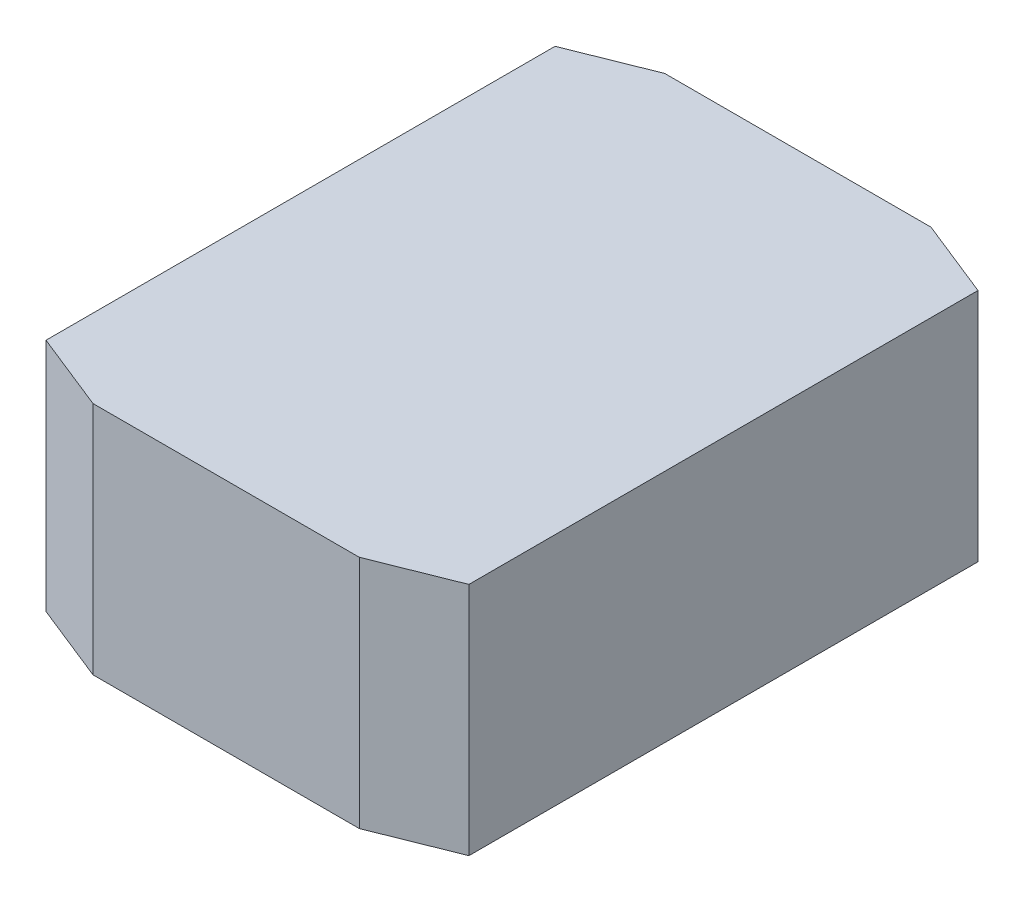
SolidWorks part; units mm, degrees
ref_plane "Piano frontale" through (0, 0, 0) normal (0, 0, 1) x (1, 0, 0)
ref_plane "Piano superiore" through (0, 0, 0) normal (0, 1, 0) x (1, 0, 0)
ref_plane "Piano destro" through (0, 0, 0) normal (1, 0, 0) x (0, 0, -1)
sketch "Schizzo2" plane through (0, 0, 0) normal (0, 1, 0) x (1, 0, 0)
  line L1 (-1350, -1825) -> (1350, -1825)
  line L2 (-1350, -1825) -> (-1350, 1825)
  line L3 (-1350, 1825) -> (1350, 1825)
  line L4 (1350, -1825) -> (1350, 1825)
  line L5 (-1350, -1825) -> (1350, 1825) construction
  line L6 (-1350, 1825) -> (1350, -1825) construction
  point P0 (0, 0)
  dimension "D1" = 3650
  dimension "D2" = 2700
extrude "Estrusione-Estrusione1" add sketch "Schizzo2" along normal blind 1500
sketch "Schizzo3" plane through (0, 1500, 0) normal (0, 1, 0) x (1, 0, 0)
  line L0 (-1350, 1825) -> (-1350, 1625)
  line L1 (-1350, 1825) -> (-1350, -1825) construction
  line L2 (-1350, 1625) -> (-850, 1825)
  line L3 (1350, 1825) -> (-1350, 1825) construction
  line L4 (-850, 1825) -> (-1350, 1825)
  dimension "D1" = 200
  dimension "D2" = 500
extrude "Taglio-Estrusione1" cut sketch "Schizzo3" against normal through all
mirror "Specchia1" about plane through (0, 0, 0) normal (0, 0, 1) of "Taglio-Estrusione1" second plane through (0, 0, 0) second plane normal (0, 1, 0)
mirror "Specchia2" about plane through (0, 0, 0) normal (1, 0, 0) of "Specchia1"
sketch "Schizzo5" plane through (0, 0, 0) normal (0, -1, 0) x (1, 0, 0)
  circle A0 centre (0, 0) radius 500
  circle A1 centre (0, 0) radius 450
  dimension "D1" = 1000
  dimension "D2" = 900
extrude "Estrusione-Estrusione3" add sketch "Schizzo5" along normal blind 300
